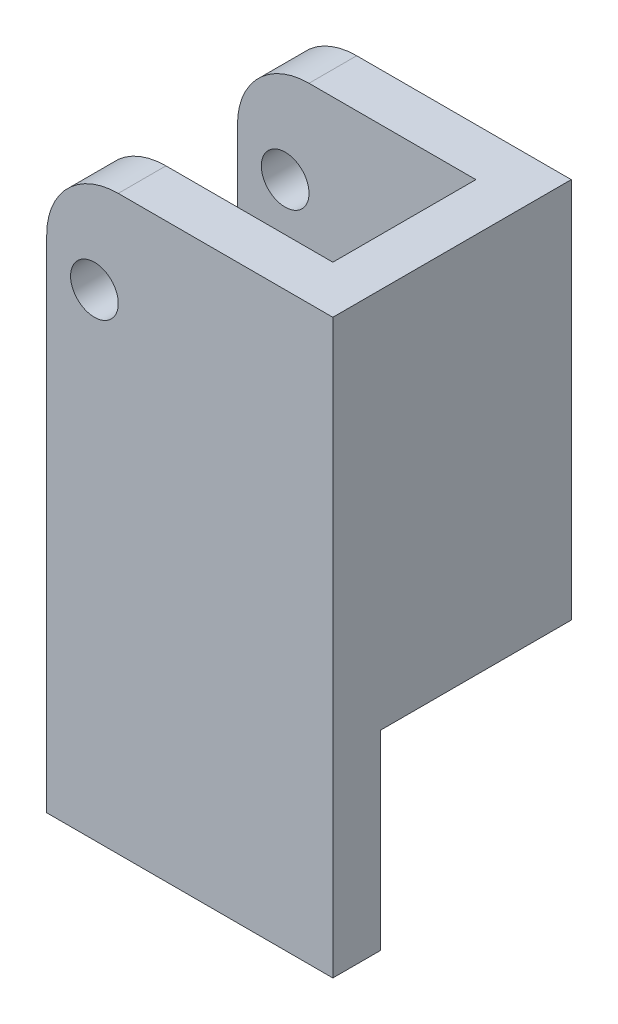
SolidWorks part; units mm, degrees
ref_plane "Front Plane" through (0, 0, 0) normal (0, 0, 1) x (1, 0, 0)
ref_plane "Top Plane" through (0, 0, 0) normal (0, 1, 0) x (1, 0, 0)
ref_plane "Right Plane" through (0, 0, 0) normal (1, 0, 0) x (0, 0, -1)
sketch "Sketch1" plane through (0, 0, 0) normal (0, 0, 1) x (1, 0, 0)
  line L1 (0, 0) -> (38.1, 0)
  line L2 (0, 0) -> (0, 76.2)
  line L3 (0, 76.2) -> (38.1, 76.2)
  line L4 (38.1, 0) -> (38.1, 76.2)
  dimension "D1" = 76.2
  dimension "D2" = 38.1
extrude "Boss-Extrude1" add sketch "Sketch1" against normal blind 31.75
sketch "Sketch2" plane through (0, 76.2, 0) normal (0, 1, 0) x (1, 0, 0)
  line L0 (0, 0) -> (0, 6.35)
  line L1 (0, 31.75) -> (0, 0) construction
  line L2 (0, 6.35) -> (31.75, 6.35)
  line L3 (31.75, 6.35) -> (31.75, 31.75)
  line L4 (38.1, 31.75) -> (0, 31.75) construction
  line L5 (38.1, 31.75) -> (38.1, 0) construction
  line L6 (31.75, 6.35) -> (31.75, 25.4) construction
  dimension "D1" = 6.35
  dimension "D2" = 6.35
  dimension "D3" = 19.05
sketch "Sketch3" plane through (0, 0, 0) normal (-1, 0, 0) x (0, 0, 1)
  line L0 (-31.75, 0) -> (-6.35, 0)
  line L1 (-31.75, 0) -> (0, 0) construction
  line L4 (-31.75, 0) -> (-31.75, 76.2)
  line L5 (-31.75, 76.2) -> (-6.35, 76.2)
  line L6 (-6.35, 0) -> (-6.35, 76.2)
  dimension "D1" = 25.4
  dimension "D2" = 76.2
extrude "Cut-Extrude2" cut sketch "Sketch3" against normal blind 31.75
sketch "Sketch4" plane through (31.75, 0, 0) normal (-1, 0, 0) x (0, 0, 1)
  line L0 (-6.35, 0) -> (-6.35, 76.2) construction
  line L1 (-31.75, 0) -> (-6.35, 0)
  line L2 (-31.75, 0) -> (-31.75, 25.4)
  line L3 (-31.75, 25.4) -> (-6.35, 25.4)
  line L4 (-6.35, 0) -> (-6.35, 25.4)
  dimension "D1" = 25.4
extrude "Cut-Extrude3" cut sketch "Sketch4" against normal through all
sketch "Sketch5" plane through (0, 76.2, 0) normal (0, 1, 0) x (1, 0, 0)
  line L0 (38.1, 31.75) -> (38.1, 0) construction
  line L1 (38.1, 0) -> (0, 0) construction
  line L2 (0, 0) -> (0, 6.35) construction
  line L3 (0, 6.35) -> (31.75, 6.35) construction
  line L4 (31.75, 6.35) -> (31.75, 31.75) construction
  line L5 (31.75, 31.75) -> (38.1, 31.75) construction
  line L6 (31.75, 6.35) -> (31.75, 25.4)
  line L7 (31.75, 31.75) -> (0, 31.75)
  line L8 (0, 31.75) -> (0, 25.4)
  line L9 (0, 25.4) -> (31.75, 25.4)
  line M6 (31.75, 31.75) -> (31.75, 6.35)
  dimension "D1" = 19.05
extrude "Boss-Extrude2" add sketch "Sketch5" against normal blind 50.8 contours L8 L9 L7 M6
sketch "Sketch6" plane through (0, 0, -31.75) normal (0, 0, -1) x (-1, 0, 0)
  line L0 (0, 76.2) -> (0, 63.5) construction
  line L1 (0, 25.4) -> (0, 76.2) construction
  line L2 (0, 63.5) -> (-6.35, 63.5) construction
  circle A0 centre (-6.35, 63.5) radius 3.175
  dimension "D3" = 6.35
  dimension "D1" = 12.7
  dimension "D2" = 6.35
extrude "Cut-Extrude4" cut sketch "Sketch6" against normal blind 50.8
fillet "Fillet2" radius 9.525 2 edges at (0, 76.2, -3.175) (0, 76.2, -28.575)
ref_plane "Plane1" through (0, 25.4, 0) normal (0, -1, 0) x (-1, 0, 0)
sketch "Sketch7" plane through (0, 25.4, 0) normal (0, -1, 0) x (-1, 0, 0)
  line L1 (0, 25.4) -> (-31.75, 25.4)
  line L2 (0, 25.4) -> (0, 6.35)
  line L3 (0, 6.35) -> (-31.75, 6.35)
  line L4 (-31.75, 25.4) -> (-31.75, 6.35)
extrude "Boss-Extrude3" add sketch "Sketch7" against normal blind 6.35
